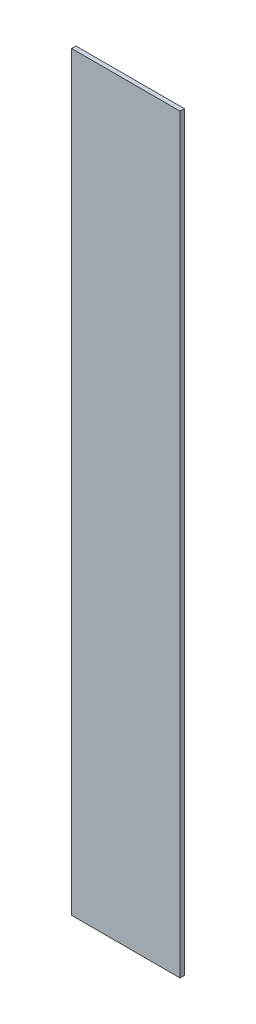
SolidWorks part; units mm, degrees
ref_plane "Front Plane" through (0, 0, 0) normal (0, 0, 1) x (1, 0, 0)
ref_plane "Top Plane" through (0, 0, 0) normal (0, 1, 0) x (1, 0, 0)
ref_plane "Right Plane" through (0, 0, 0) normal (1, 0, 0) x (0, 0, -1)
sketch "Sketch1" plane through (0, 0, 0) normal (0, 1, 0) x (1, 0, 0)
  line L1 (25, -1) -> (-25, -1)
  line L2 (25, -1) -> (25, 1)
  line L3 (25, 1) -> (-25, 1)
  line L4 (-25, -1) -> (-25, 1)
  line L5 (25, -1) -> (-25, 1) construction
  line L6 (25, 1) -> (-25, -1) construction
  point P0 (0, 0)
extrude "Boss-Extrude1" add sketch "Sketch1" along normal blind 200 and the other way up to surface (146 mm away)
